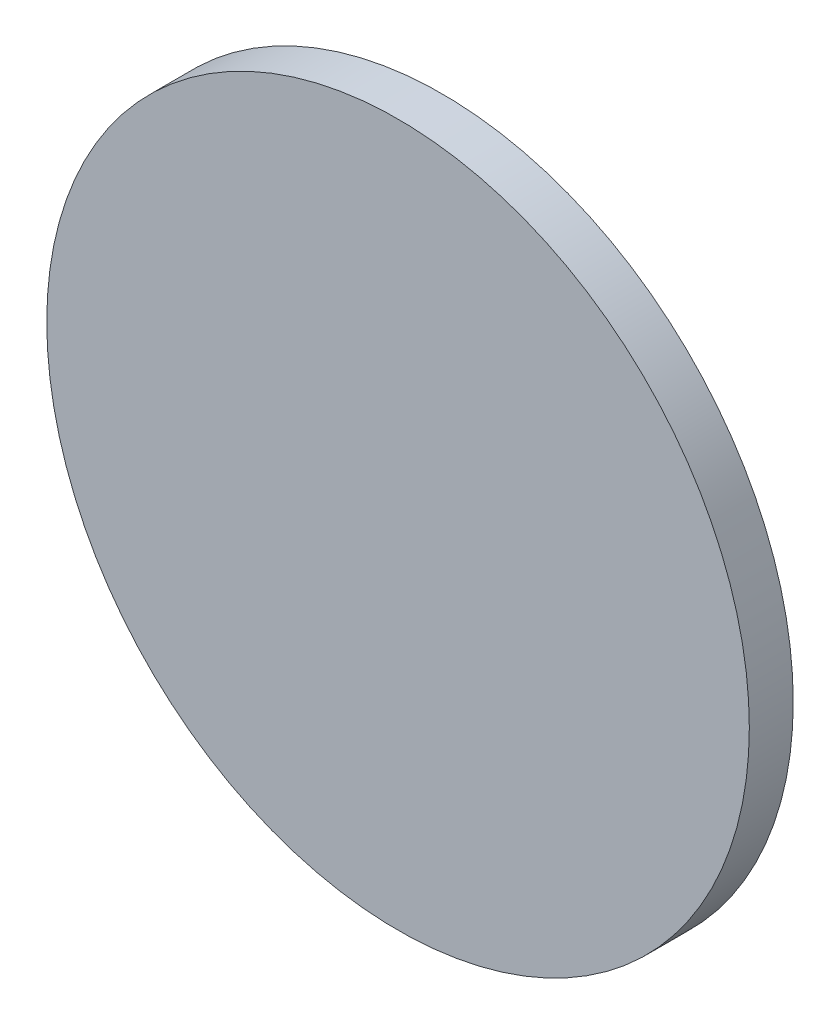
SolidWorks part; units mm, degrees
ref_plane "前视基准面" through (0, 0, 0) normal (0, 0, 1) x (1, 0, 0)
ref_plane "上视基准面" through (0, 0, 0) normal (0, 1, 0) x (1, 0, 0)
ref_plane "右视基准面" through (0, 0, 0) normal (1, 0, 0) x (0, 0, -1)
sketch "草图1" plane through (0, 0, 0) normal (0, 0, 1) x (1, 0, 0)
  circle A0 centre (0, 0) radius 29.25
  circle A1 centre (0, 0) radius 23.25
  circle A2 centre (0, 0) radius 24.75
  circle A3 centre (0, 0.7597) radius 36.75
  dimension "D1" = 58.5
  dimension "D2" = 73.5
  dimension "D3" = 46.5
  dimension "D4" = 49.5
sketch "草图2" plane through (0, 0, 0) normal (0, 0, 1) x (1, 0, 0)
  circle A0 centre (0, 0.7597) radius 40
  dimension "D1" = 80
extrude "凸台-拉伸1" add sketch "草图2" along normal blind 5
extrude "切除-拉伸1" cut sketch "草图1" along normal blind 2 contours A0 | A3 | A1 | A2
